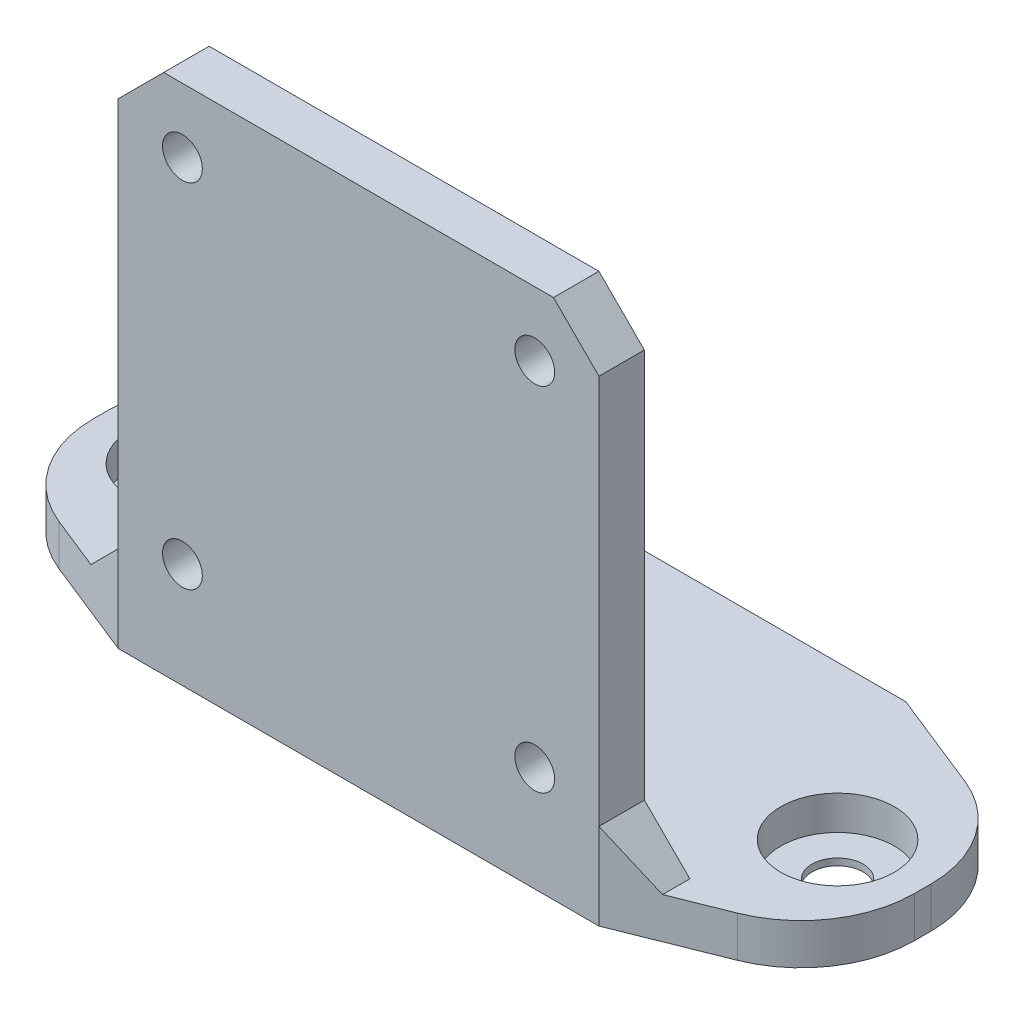
SolidWorks part; units mm, degrees
material "ABS"
ref_plane "Piano frontale" through (0, 0, 0) normal (0, 0, 1) x (1, 0, 0)
ref_plane "Piano superiore" through (0, 0, 0) normal (0, 1, 0) x (1, 0, 0)
ref_plane "Piano destro" through (0, 0, 0) normal (1, 0, 0) x (0, 0, -1)
sketch "Schizzo2" plane through (0, 0, 0) normal (0, 1, 0) x (1, 0, 0)
  line L1 (0, 0) -> (72.3, 0)
  line L2 (0, 0) -> (0, -27)
  line L3 (0, -27) -> (72.3, -27)
  line L4 (72.3, 0) -> (72.3, -27)
  dimension "D1" = 27
  dimension "D2" = 72.3
extrude "Estrusione-Estrusione1" add sketch "Schizzo2" along normal blind 3.6
sketch "Schizzo3" plane through (0, 3.6, 0) normal (0, 1, 0) x (1, 0, 0)
  line L0 (0, -27) -> (72.3, -27) construction
  line L1 (15, -27) -> (57.3, -27)
  line L2 (15, -27) -> (15, -23)
  line L3 (15, -23) -> (57.3, -23)
  line L4 (57.3, -27) -> (57.3, -23)
  line L5 (36.15, -23) -> (36.15, -27) construction
  dimension "D1" = 42.3
  dimension "D2" = 4
extrude "Estrusione-Estrusione2" add sketch "Schizzo3" along normal blind 42.3
sketch "Schizzo4" plane through (0, 0, 27) normal (0, 0, 1) x (1, 0, 0)
  line L0 (15, 45.9) -> (57.3, 45.9) construction
  line L1 (20.65, 9.25) -> (51.65, 9.25) construction
  line L2 (20.65, 9.25) -> (20.65, 40.25) construction
  line L3 (20.65, 40.25) -> (51.65, 40.25) construction
  line L4 (51.65, 9.25) -> (51.65, 40.25) construction
  line L5 (15, 45.9) -> (15, 3.6) construction
  circle A0 centre (20.65, 40.25) radius 1.75
  circle A1 centre (51.65, 40.25) radius 1.75
  circle A2 centre (51.65, 9.25) radius 1.75
  circle A3 centre (20.65, 9.25) radius 1.75
  dimension "D4" = 3.5
  dimension "D1" = 5.65
  dimension "D2" = 31
  dimension "D3" = 5.65
extrude "Taglio-Estrusione1" cut sketch "Schizzo4" against normal blind 42.3
hole_wizard "Foro lamato per Vite M4 a testa cilindrica-2" positions "Schizzo5" profile "Schizzo7" counterbore size "M4" standard "DIN"
sketch "Schizzo5" plane through (0, 3.6, 0) normal (0, 1, 0) x (1, 0, 0)
  line L0 (7.5, -13.5) -> (0, -13.5) construction
  line L1 (0, 0) -> (0, -27) construction
  line L2 (0, -13.5) -> (64.8, -13.5) construction
  line L4 (7.5, -27) -> (7.5, -13.5) construction
  line L5 (0, -27) -> (15, -27) construction
  line L7 (64.8, -27) -> (64.8, -13.5) construction
  line L8 (57.3, -27) -> (72.3, -27) construction
  point P0 (7.5, -13.5)
  point P2 (64.8, -13.5)
sketch "Schizzo7" plane through (7.5, 3.6, 13.5) normal (1, 0, 0) x (0, 0, 1)
  line L0 (0, 0) -> (0, 10.3519)
  line L1 (0, 10.3519) -> (2.25, 9)
  line L2 (2.25, 9) -> (2.25, 3)
  line L3 (2.25, 3) -> (5, 3)
  line L4 (5, 3) -> (5, 0)
  line L5 (5, 0) -> (0, 0)
  line L10 (0, 10.3519) -> (-2.25, 9) construction
  line L11 (0, -6.35) -> (0, 107.95) construction
  dimension "Hole Dia." = 4.5
  dimension "Hole Depth" = 9
  dimension "C'Bore Dia." = 10
  dimension "C'Bore Depth" = 3
  dimension "Drill Angle" = 118
sketch "Schizzo8" plane through (0, 3.6, 0) normal (0, 1, 0) x (1, 0, 0)
  line L0 (15, -27) -> (0, -21)
  line L1 (0, 0) -> (0, -27) construction
  line L2 (0, -21) -> (0, -27)
  line L3 (0, -27) -> (15, -27)
  line L4 (0, -6) -> (0, 0)
  line L5 (0, 0) -> (15, 0)
  line L6 (72.3, 0) -> (0, 0) construction
  line L7 (15, 0) -> (0, -6)
  line L8 (57.3, 0) -> (72.3, 0)
  line L9 (72.3, 0) -> (72.3, -6)
  line L10 (72.3, -27) -> (72.3, 0) construction
  line L11 (72.3, -6) -> (57.3, 0)
  line L12 (57.3, -27) -> (72.3, -27)
  line L13 (72.3, -27) -> (72.3, -21)
  line L14 (72.3, -21) -> (57.3, -27)
  line L15 (15, -27) -> (15, 0) construction
  line L16 (57.3, -27) -> (57.3, 0) construction
  dimension "D1" = 15
extrude "Taglio-Estrusione2" cut sketch "Schizzo8" against normal blind 42.3
chamfer "Smusso1" distance 4 angle 45 2 edges at (57.3, 45.9, 25) (15, 45.9, 25)
fillet "Raccordo1" radius 10 4 edges at (72.3, 1.8, 6) (72.3, 1.8, 21) (0, 1.8, 6) (0, 1.8, 21)
chamfer "Smusso2" distance 4 angle 45 2 edges at (57.3, 3.6, 25) (15, 3.6, 25)
